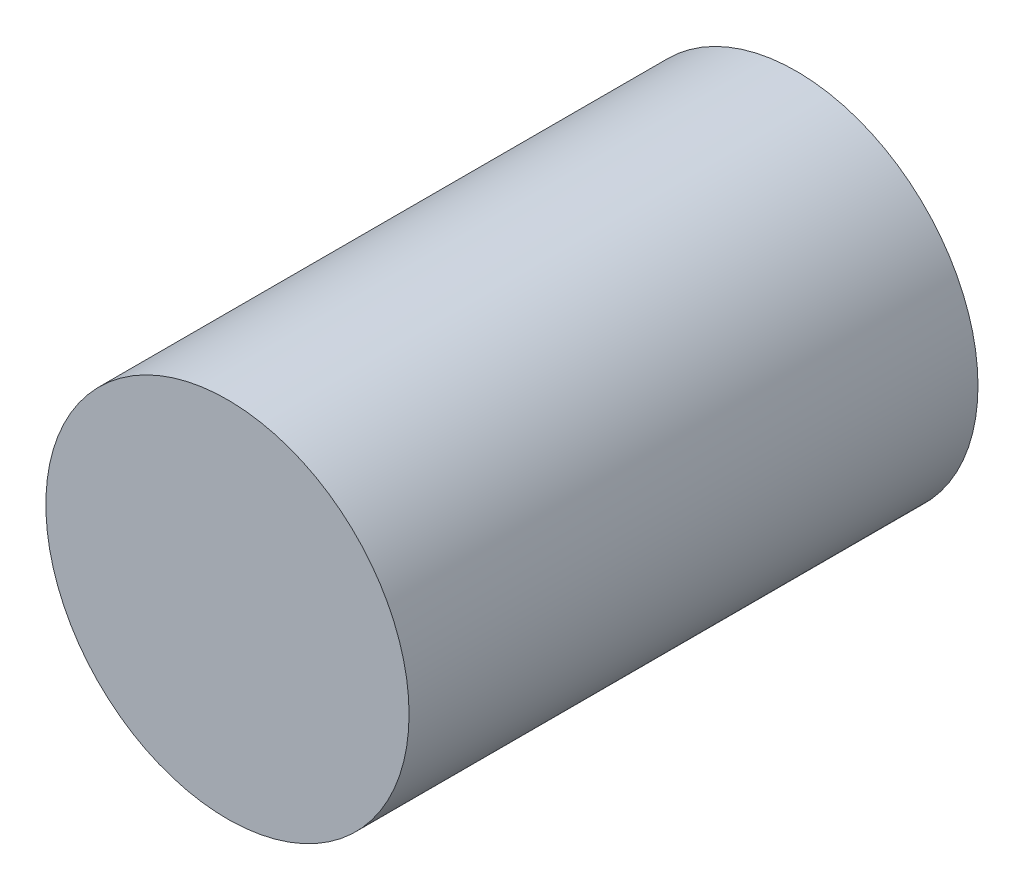
SolidWorks part; units mm, degrees
material "AISI Type A2 Tool Steel"
ref_plane "Front Plane" through (0, 0, 0) normal (0, 0, 1) x (1, 0, 0)
ref_plane "Top Plane" through (0, 0, 0) normal (0, 1, 0) x (1, 0, 0)
ref_plane "Right Plane" through (0, 0, 0) normal (1, 0, 0) x (0, 0, -1)
sketch "Sketch1" plane through (0, 0, 0) normal (0, 0, 1) x (1, 0, 0)
  circle A0 centre (0, 0) radius 4.67
  dimension "D1" = 9.34
extrude "Boss-Extrude1" add sketch "Sketch1" along normal blind 14.63
